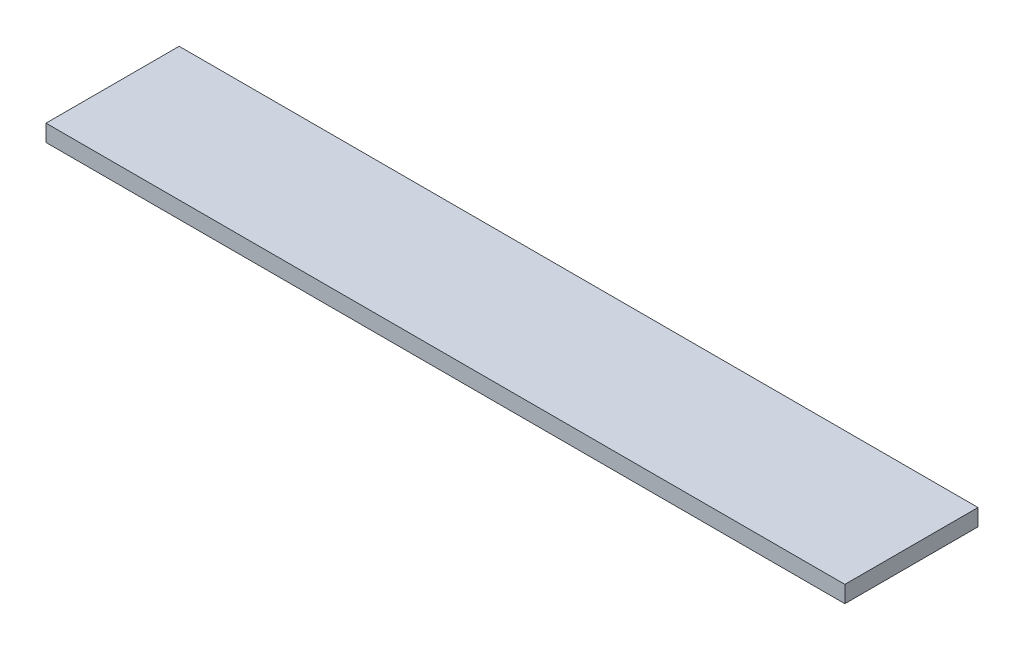
SolidWorks part; units mm, degrees
material "Thornel Mat VMA"
ref_plane "Front" through (0, 0, 0) normal (0, 0, 1) x (1, 0, 0)
ref_plane "Top" through (0, 0, 0) normal (0, 1, 0) x (1, 0, 0)
ref_plane "Right" through (0, 0, 0) normal (1, 0, 0) x (0, 0, -1)
sketch "Sketch1" plane through (0, 0, 0) normal (0, 1, 0) x (1, 0, 0)
  line L1 (-38.1, -6.35) -> (38.1, -6.35)
  line L2 (-38.1, -6.35) -> (-38.1, 6.35)
  line L3 (-38.1, 6.35) -> (38.1, 6.35)
  line L4 (38.1, -6.35) -> (38.1, 6.35)
  line L5 (-38.1, -6.35) -> (38.1, 6.35) construction
  line L6 (-38.1, 6.35) -> (38.1, -6.35) construction
  point P0 (0, 0)
  dimension "D1" = 76.2
  dimension "D2" = 12.7
extrude "Boss-Extrude1" add sketch "Sketch1" along normal blind 1.6002
